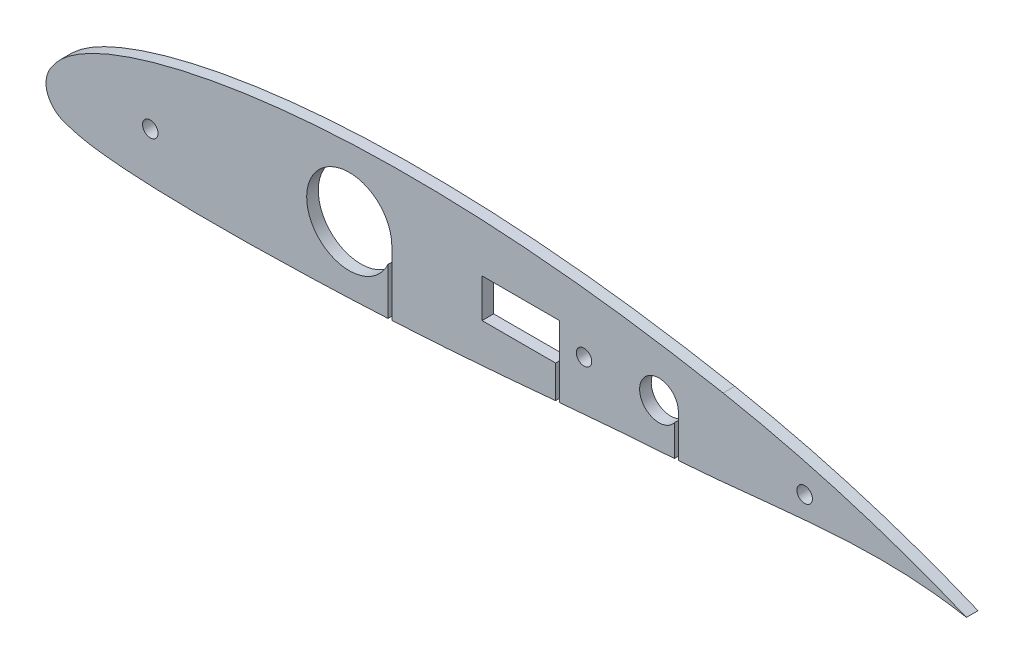
SolidWorks part; units mm, degrees
ref_plane "Front" through (0, 0, 0) normal (0, 0, 1) x (1, 0, 0)
ref_plane "Top" through (0, 0, 0) normal (0, 1, 0) x (1, 0, 0)
ref_plane "Right" through (0, 0, 0) normal (1, 0, 0) x (0, 0, -1)
sketch "Sketch1" plane through (0, 0, 0) normal (0, 0, 1) x (1, 0, 0)
  line L0 (-71.0818, 4.3261) -> (-69.7318, 4.384)
  line L1 (-36.1092, 25.7451) -> (-16.1092, 25.7451)
  line L2 (-36.1092, 25.7451) -> (-36.1092, 15.7451)
  line L3 (-36.1092, 15.7451) -> (-17.1092, 15.7451)
  line L4 (-16.1092, 25.7451) -> (-16.1092, 19.2966)
  line L17 (-50.0108, 5.3795) -> (-47.31, 5.537)
  line L18 (-59.4068, 20.7451) -> (-59.4068, 4.8701)
  line L19 (-60.4068, 16.1625) -> (-60.4068, 4.8198)
  line L20 (-16.1092, 19.2966) -> (-16.1092, 7.7889)
  line L21 (-17.1092, 15.7451) -> (-17.1092, 7.7043)
  line L22 (14.5932, 20.7451) -> (14.5932, 10.502)
  line L23 (13.5932, 17.7451) -> (13.5932, 10.4166)
  circle A0 centre (9.5932, 20.7451) radius 5 construction
  circle A1 centre (-70.4068, 20.7451) radius 11 construction
  arc A2 (14.5932, 20.7451) -> (13.5932, 17.7451) centre (9.5932, 20.7451) ccw
  arc A3 (-59.4068, 20.7451) -> (-60.4068, 16.1625) centre (-70.4068, 20.7451) ccw
  circle A4 centre (-121.8028, 15.7701) radius 2
  circle A5 centre (59.3391, 20.7451) radius 2
  circle A6 centre (-9.7688, 20.7451) radius 2
  spline S0 degree 3 poles (-47.31, 5.537) (-47.1289, 5.5477) (-41.7126, 5.8685) (-31.641, 6.5306) (-21.7599, 7.3125) (-17.1092, 7.7043) knots 0.708178 0.708178 0.708178 0.708178 0.709076 0.735036 0.758139 0.758139 0.758139 0.758139
  spline S1 degree 3 poles (38.2682, 12.331) (41.3825, 12.5361) (49.4822, 13.0301) (62.2579, 13.616) (76.1865, 13.9414) (88.9177, 13.8805) (100.1456, 13.479) (109.7496, 12.7199) (117.0779, 11.8175) (122.9528, 10.7041) (125.3195, 10.2685) (128.1323, 9.5094) (125.6545, 10.4145) (123.8171, 11.2948) (119.5362, 12.9981) (114.2976, 14.7106) (107.4982, 16.6465) (99.4453, 18.7417) (90.1462, 20.9802) (79.7583, 23.308) (68.4053, 25.6742) (56.237, 28.0241) (43.3949, 30.2811) (30.0199, 32.3736) (16.2369, 34.2202) (2.1651, 35.7556) (-12.0689, 36.9617) (-26.3399, 37.814) (-40.517, 38.2756) (-54.4758, 38.3382) (-68.093, 38.0028) (-81.2543, 37.2555) (-93.8487, 36.1153) (-105.7717, 34.6098) (-116.9218, 32.7863) (-127.197, 30.6681) (-136.5081, 28.3232) (-144.7684, 25.7804) (-151.9085, 23.1088) (-157.8744, 20.3632) (-162.6123, 17.6138) (-166.1496, 14.8861) (-168.3325, 12.3394) (-169.3807, 10.5404) (-169.4245, 9.1539) (-168.5264, 7.651) (-165.5653, 6.7783) (-161.3678, 5.642) (-155.4843, 4.8321) (-148.1552, 4.1352) (-139.387, 3.6549) (-129.2981, 3.3595) (-117.9909, 3.2485) (-105.595, 3.3258) (-92.2488, 3.5829) (-80.6385, 3.9408) (-73.4941, 4.2239) (-71.0818, 4.3261) knots 0.852065 0.852065 0.852065 0.852065 0.867514 0.892232 0.915364 0.936485 0.9552 0.971104 0.983751 0.992813 0.998211 1 1.001694 1.006395 1.013462 1.022754 1.034367 1.048191 1.064031 1.081681 1.100894 1.121432 1.143025 1.165434 1.188439 1.211855 1.235496 1.259144 1.282615 1.305702 1.328232 1.35003 1.370944 1.390817 1.409506 1.426857 1.442733 1.457018 1.469615 1.48045 1.489472 1.49673 1.502329 1.506256 1.506442 1.509182 1.513914 1.521178 1.530944 1.543145 1.55767 1.574384 1.59311 1.613638 1.635744 1.659184 1.671136 1.671136 1.671136 1.671136
  spline S2 degree 3 poles (-69.7318, 4.384) (-67.6432, 4.4746) (-64.5347, 4.6167) (-61.4267, 4.7688) (-60.4068, 4.8198) knots 0.673365 0.673365 0.673365 0.673365 0.683714 0.688769 0.688769 0.688769 0.688769
  spline S3 degree 3 poles (-59.4068, 4.8701) (-56.2742, 5.029) (-53.1422, 5.1985) (-50.0108, 5.3795) knots 0.690421 0.690421 0.690421 0.690421 0.705947 0.705947 0.705947 0.705947
  spline S4 degree 3 poles (-16.1092, 7.7889) (-15.7801, 7.8169) (-10.0657, 8.3045) (-0.1675, 9.2094) (9.4042, 10.0578) (13.5932, 10.4166) knots 0.759795 0.759795 0.759795 0.759795 0.76143 0.788184 0.808996 0.808996 0.808996 0.808996
  spline S5 degree 3 poles (14.5932, 10.502) (15.48, 10.5775) (21.719, 11.1047) (29.6096, 11.7304) (36.6179, 12.2199) (38.2682, 12.331) knots 0.810652 0.810652 0.810652 0.810652 0.815057 0.841645 0.849832 0.849832 0.849832 0.849832
  point P24 (-36.1092, 20.7451)
  dimension "D1" = 4
  dimension "D2" = 20
  dimension "D3" = 10
  dimension "D4" = 1
  dimension "D6" = 1
sketch "Sketch5" plane through (0, 0, 0) normal (0, 0, 1) x (1, 0, 0)
  line L0 (-59.4068, 20.7451) -> (-59.4068, 4.1275)
  line L2 (-36.1092, 25.7451) -> (-36.1092, 15.7451) construction
  line L3 (-36.1092, 15.7451) -> (-17.1092, 15.7451) construction
  line L4 (-36.1092, 25.7451) -> (-16.1092, 25.7451) construction
  line L5 (-16.1092, 25.7451) -> (-16.1092, 7.4051)
  line L6 (-36.1092, 25.7451) -> (-36.1092, 15.7451)
  line L7 (-36.1092, 15.7451) -> (-17.1092, 15.7451)
  line L8 (-36.1092, 25.7451) -> (-16.1092, 25.7451)
  line L9 (-17.1092, 15.7451) -> (-17.1092, 7.3158)
  line L10 (-60.4068, 16.1625) -> (-60.4068, 4.0747)
  line L11 (14.5932, 20.7451) -> (14.5932, 9.7879)
  line L12 (13.5932, 17.7451) -> (13.5932, 9.7247)
  circle A1 centre (-121.8028, 15.7701) radius 2 construction
  arc A2 (14.5932, 20.7451) -> (13.5932, 17.7451) centre (9.5932, 20.7451) ccw construction
  circle A3 centre (-9.7688, 20.7451) radius 2 construction
  arc A4 (-59.4068, 20.7451) -> (-60.4068, 16.1625) centre (-70.4068, 20.7451) ccw construction
  circle A5 centre (47.2241, 18.5105) radius 2
  circle A6 centre (-121.8028, 15.7701) radius 2
  arc A7 (14.5932, 20.7451) -> (13.5932, 17.7451) centre (9.5932, 20.7451) ccw
  circle A8 centre (-9.7688, 20.7451) radius 2
  arc A9 (-59.4068, 20.7451) -> (-60.4068, 16.1625) centre (-70.4068, 20.7451) ccw
  spline S0 degree 3 poles (74.5756, 12.9846) (76.6592, 12.4224) (74.8238, 13.0928) (73.4627, 13.7448) (70.2918, 15.0066) (66.4113, 16.2751) (61.3747, 17.7091) (55.4095, 19.2611) (48.5214, 20.9192) (40.8266, 22.6435) (32.417, 24.3963) (23.4035, 26.137) (13.8907, 27.8088) (3.9834, 29.3588) (-6.2263, 30.7267) (-16.6498, 31.864) (-27.1936, 32.7574) (-37.7647, 33.3888) (-48.2662, 33.7307) (-58.606, 33.777) (-68.6928, 33.5286) (-78.442, 32.975) (-87.7711, 32.1304) (-96.603, 31.0153) (-104.8623, 29.6645) (-112.4736, 28.0955) (-119.3707, 26.3585) (-125.4895, 24.4749) (-130.7784, 22.4959) (-135.1976, 20.4622) (-138.7072, 18.4256) (-141.3274, 16.4051) (-142.9444, 14.5186) (-143.7208, 13.1861) (-143.7533, 12.159) (-143.088, 11.0457) (-140.8945, 10.3993) (-137.7853, 9.5576) (-133.4272, 8.9577) (-127.9982, 8.4415) (-121.5032, 8.0857) (-114.03, 7.8669) (-105.6543, 7.7846) (-96.4721, 7.8419) (-86.5861, 8.0324) (-76.1045, 8.3554) (-65.1406, 8.8243) (-53.8056, 9.4267) (-42.2005, 10.1882) (-30.3997, 11.1311) (-18.4747, 12.2197) (-6.5174, 13.2738) (5.3171, 14.2106) (16.842, 14.9588) (27.8634, 15.4643) (38.1808, 15.7053) (47.6113, 15.6602) (55.9283, 15.3628) (63.0424, 14.8005) (68.4707, 14.1321) (72.8225, 13.3073) (74.5756, 12.9846) (76.6592, 12.4224) (74.8238, 13.0928) knots -0.016249 -0.007187 -0.001789 0 0.001694 0.006395 0.013462 0.022754 0.034367 0.048191 0.064031 0.081681 0.100894 0.121432 0.143025 0.165434 0.188439 0.211855 0.235496 0.259144 0.282615 0.305702 0.328232 0.35003 0.370944 0.390817 0.409506 0.426857 0.442733 0.457018 0.469615 0.48045 0.489472 0.49673 0.502329 0.506256 0.506442 0.509182 0.513914 0.521178 0.530944 0.543145 0.55767 0.574384 0.59311 0.613638 0.635744 0.659184 0.683714 0.709076 0.735036 0.76143 0.788184 0.815057 0.841645 0.867514 0.892232 0.915364 0.936485 0.9552 0.971104 0.983751 0.992813 0.998211 1 1.001694 1.006395 1.013462 only from (76.2599, 12.5498) to (76.2599, 12.5498) construction
  spline S1 degree 3 poles (-16.1092, 12.4249) (-12.8979, 12.7106) (-5.7224, 13.3367) (5.3171, 14.2106) (16.842, 14.9588) (27.8634, 15.4643) (38.1808, 15.7053) (47.6113, 15.6602) (55.9283, 15.3628) (63.0424, 14.8005) (68.4707, 14.1321) (72.8225, 13.3073) (74.5756, 12.9846) (76.6592, 12.4224) (74.8238, 13.0928) (73.4627, 13.7448) (70.2918, 15.0066) (66.4113, 16.2751) (61.3747, 17.7091) (55.4095, 19.2611) (48.5214, 20.9192) (40.8266, 22.6435) (32.417, 24.3963) (23.4035, 26.137) (13.8907, 27.8088) (3.9834, 29.3588) (-6.2263, 30.7267) (-16.6498, 31.864) (-27.1936, 32.7574) (-37.7647, 33.3888) (-48.2662, 33.7307) (-58.606, 33.777) (-68.6928, 33.5286) (-78.442, 32.975) (-87.7711, 32.1304) (-96.603, 31.0153) (-104.8623, 29.6645) (-112.4736, 28.0955) (-119.3707, 26.3585) (-125.4895, 24.4749) (-130.7784, 22.4959) (-135.1976, 20.4622) (-138.7072, 18.4256) (-141.3274, 16.4051) (-142.9444, 14.5186) (-143.7208, 13.1861) (-143.7533, 12.159) (-143.088, 11.0457) (-140.8945, 10.3993) (-137.7853, 9.5576) (-133.4272, 8.9577) (-127.9982, 8.4415) (-121.5032, 8.0857) (-114.03, 7.8669) (-105.6543, 7.7846) (-96.4721, 7.8419) (-86.5861, 8.0324) (-76.1045, 8.3554) (-65.1406, 8.8243) (-53.8056, 9.4267) (-42.2005, 10.1882) (-30.3997, 11.1311) (-22.0186, 11.8962) (-17.5701, 12.2946) (-17.1092, 12.3357) knots 0.793512 0.793512 0.793512 0.793512 0.815057 0.841645 0.867514 0.892232 0.915364 0.936485 0.9552 0.971104 0.983751 0.992813 0.998211 1 1.001694 1.006395 1.013462 1.022754 1.034367 1.048191 1.064031 1.081681 1.100894 1.121432 1.143025 1.165434 1.188439 1.211855 1.235496 1.259144 1.282615 1.305702 1.328232 1.35003 1.370944 1.390817 1.409506 1.426857 1.442733 1.457018 1.469615 1.48045 1.489472 1.49673 1.502329 1.506256 1.506442 1.509182 1.513914 1.521178 1.530944 1.543145 1.55767 1.574384 1.59311 1.613638 1.635744 1.659184 1.683714 1.709076 1.735036 1.76143 1.788184 1.791276 1.791276 1.791276 1.791276 construction
  spline S2 degree 3 poles (-59.4068, 4.1275) (-56.0183, 4.3081) (-47.9374, 4.7793) (-35.1604, 5.7012) (-24.5369, 6.6488) (-18.5364, 7.1881) (-17.1925, 7.3083) (-17.1092, 7.3158) knots 1.696188 1.696188 1.696188 1.696188 1.71875 1.75 1.78125 1.78972 1.79028 1.79028 1.79028 1.79028
  spline S3 degree 3 poles (-16.1092, 7.4051) (-16.0258, 7.4125) (-13.0528, 7.6774) (-5.4378, 8.3453) (3.8546, 9.0827) (10.7794, 9.5499) (13.069, 9.6927) (13.5932, 9.7247) knots 0.79252 0.79252 0.79252 0.79252 0.79308 0.8125 0.84375 0.855659 0.859195 0.859195 0.859195 0.859195
  spline S4 degree 3 poles (14.5932, 9.7879) (39.458, 11.4054) (63.9142, 16.5218) (89.0016, 11.9046) knots 0.013226 0.013226 0.013226 0.013226 1 1 1 1
  spline S5 degree 2 poles (23.275, 31.217) (57.3229, 25.0728) (89.0016, 11.9046) knots 0 0 0 1 1 1
  spline S6 degree 3 poles (26.1705, 30.681) (25.0717, 30.8873) (21.6526, 31.5191) (15.9022, 32.5263) (6.579, 34.033) (-5.1331, 35.6661) (-19.2486, 37.1613) (-33.4033, 38.2059) (-47.6089, 38.7589) (-61.832, 38.7789) (-73.7055, 38.3054) (-83.1964, 37.5818) (-90.3084, 36.8561) (-97.4055, 35.9335) (-104.4902, 34.7993) (-111.5574, 33.4138) (-117.418, 32.0272) (-122.0964, 30.7377) (-125.5958, 29.6654) (-129.0783, 28.4751) (-132.5514, 27.136) (-135.4386, 25.8622) (-137.7342, 24.7128) (-139.457, 23.7687) (-141.1834, 22.7096) (-142.6152, 21.7138) (-143.778, 20.7916) (-144.6423, 20.0314) (-145.4885, 19.1918) (-146.2955, 18.2765) (-146.9249, 17.446) (-147.4021, 16.7479) (-147.8615, 15.9873) (-148.2575, 15.1336) (-148.5253, 14.2783) (-148.6524, 13.6789) (-148.7151, 13.1462) (-148.7436, 12.7703) (-148.7363, 12.1171) (-148.6411, 11.3518) (-148.4112, 10.4824) (-147.8996, 9.3327) (-147.1312, 8.2534) (-146.0906, 7.2803) (-145.0342, 6.6043) (-144.0994, 6.1764) (-143.3279, 5.9073) (-142.7444, 5.737) (-142.3247, 5.6181) (-141.7124, 5.4466) (-140.9481, 5.2409) (-139.6795, 4.9232) (-138.0064, 4.5759) (-136.0794, 4.2786) (-134.2325, 4.0482) (-132.4228, 3.849) (-130.0057, 3.6169) (-126.9964, 3.3867) (-123.4041, 3.1871) (-119.8389, 3.041) (-116.2798, 2.9354) (-111.5478, 2.8404) (-105.6422, 2.7932) (-98.5712, 2.8266) (-91.5114, 2.9315) (-84.4586, 3.0969) (-75.0574, 3.391) (-67.0431, 3.7356) (-61.3782, 4.0239) (-60.4068, 4.0747) knots 1.117594 1.117594 1.117594 1.117594 1.125 1.140625 1.15625 1.1875 1.21875 1.25 1.28125 1.3125 1.34375 1.359375 1.375 1.390625 1.40625 1.421875 1.4375 1.445312 1.453125 1.460938 1.46875 1.476562 1.480469 1.484375 1.488281 1.492188 1.494141 1.496094 1.498047 1.5 1.501953 1.50293 1.503906 1.504883 1.505371 1.505859 1.506104 1.506348 1.506592 1.506836 1.507324 1.507812 1.508789 1.509766 1.510742 1.511719 1.512695 1.513672 1.514648 1.515625 1.517578 1.519531 1.523438 1.527344 1.53125 1.535156 1.539062 1.546875 1.554688 1.5625 1.570312 1.578125 1.59375 1.609375 1.625 1.640625 1.65625 1.6875 1.693968 1.693968 1.693968 1.693968
  spline S9 degree 3 poles (38.2682, 12.331) (41.3825, 12.5361) (49.4822, 13.0301) (62.2579, 13.616) (76.1865, 13.9414) (88.9177, 13.8805) (100.1456, 13.479) (109.7496, 12.7199) (117.0779, 11.8175) (122.9528, 10.7041) (125.3195, 10.2685) (128.1323, 9.5094) (125.6545, 10.4145) (123.8171, 11.2948) (119.5362, 12.9981) (114.2976, 14.7106) (107.4982, 16.6465) (99.4453, 18.7417) (90.1462, 20.9802) (79.7583, 23.308) (68.4053, 25.6742) (56.237, 28.0241) (43.3949, 30.2811) (30.0199, 32.3736) (16.2369, 34.2202) (2.1651, 35.7556) (-12.0689, 36.9617) (-26.3399, 37.814) (-40.517, 38.2756) (-54.4758, 38.3382) (-68.093, 38.0028) (-81.2543, 37.2555) (-93.8487, 36.1153) (-105.7717, 34.6098) (-116.9218, 32.7863) (-127.197, 30.6681) (-136.5081, 28.3232) (-144.7684, 25.7804) (-151.9085, 23.1088) (-157.8744, 20.3632) (-162.6123, 17.6138) (-166.1496, 14.8861) (-168.3325, 12.3394) (-169.3807, 10.5404) (-169.4245, 9.1539) (-168.5264, 7.651) (-165.5653, 6.7783) (-161.3678, 5.642) (-155.4843, 4.8321) (-148.1552, 4.1352) (-139.387, 3.6549) (-129.2981, 3.3595) (-117.9909, 3.2485) (-105.595, 3.3258) (-92.2488, 3.5829) (-80.6385, 3.9408) (-73.4941, 4.2239) (-71.0818, 4.3261) knots 0.852065 0.852065 0.852065 0.852065 0.867514 0.892232 0.915364 0.936485 0.9552 0.971104 0.983751 0.992813 0.998211 1 1.001694 1.006395 1.013462 1.022754 1.034367 1.048191 1.064031 1.081681 1.100894 1.121432 1.143025 1.165434 1.188439 1.211855 1.235496 1.259144 1.282615 1.305702 1.328232 1.35003 1.370944 1.390817 1.409506 1.426857 1.442733 1.457018 1.469615 1.48045 1.489472 1.49673 1.502329 1.506256 1.506442 1.509182 1.513914 1.521178 1.530944 1.543145 1.55767 1.574384 1.59311 1.613638 1.635744 1.659184 1.671136 1.671136 1.671136 1.671136 construction
  point P2 (0, 0)
  point P4 (13.5932, 9.7247)
  point P11 (23.275, 31.217)
extrude "Boss-Extrude1" add sketch "Sketch5" along normal blind 3 contours S5 S6 L10 A9 L0 S2 L9 L7 L6 L8 L5 S3 L12 A7 L11 S4 A5 A6 A8
sketch "Sketch6" plane through (0, 0, 3) normal (0, 0, 1) x (1, 0, 0)
  line L0 (-36.1092, 25.7451) -> (-36.1092, 15.7451) construction
  line L1 (-153.7834, -4.2549) -> (96.2166, -4.2549)
  line L2 (-153.7834, -4.2549) -> (-153.7834, 45.7451)
  line L3 (-153.7834, 45.7451) -> (96.2166, 45.7451)
  line L4 (96.2166, -4.2549) -> (96.2166, 45.7451)
  point P4 (-153.7834, 20.7451)
  point P7 (-36.1092, 20.7451)
  point P8 (-153.7834, 45.7451)
  dimension "D1" = 50
  dimension "D2" = 250
